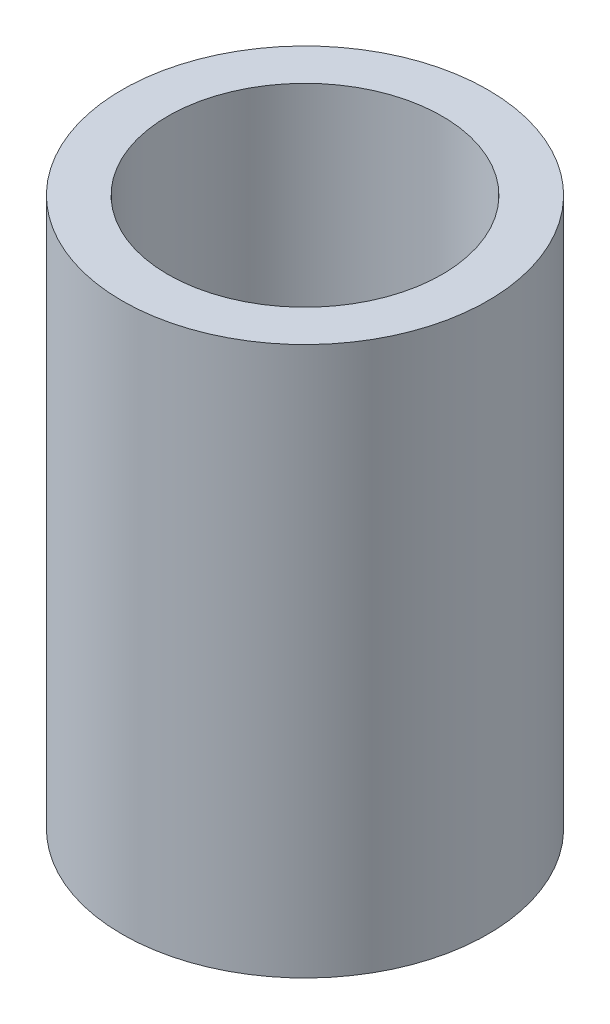
SolidWorks part; units mm, degrees
ref_plane "Plan de face" through (0, 0, 0) normal (0, 0, 1) x (1, 0, 0)
ref_plane "Plan de dessus" through (0, 0, 0) normal (0, 1, 0) x (1, 0, 0)
ref_plane "Plan de droite" through (0, 0, 0) normal (1, 0, 0) x (0, 0, -1)
sketch "Esquisse1" plane through (0, 0, 0) normal (0, 1, 0) x (1, 0, 0)
  circle A0 centre (0, 0) radius 20
  dimension "D1" = 40
extrude "Boss.-Extru.1" add sketch "Esquisse1" along normal blind 60
sketch "Esquisse2" plane through (0, 60, 0) normal (0, 1, 0) x (1, 0, 0)
  circle A0 centre (0, 0) radius 15
  dimension "D1" = 30
extrude "Enlèv. mat.-Extru.1" cut sketch "Esquisse2" against normal blind 55
